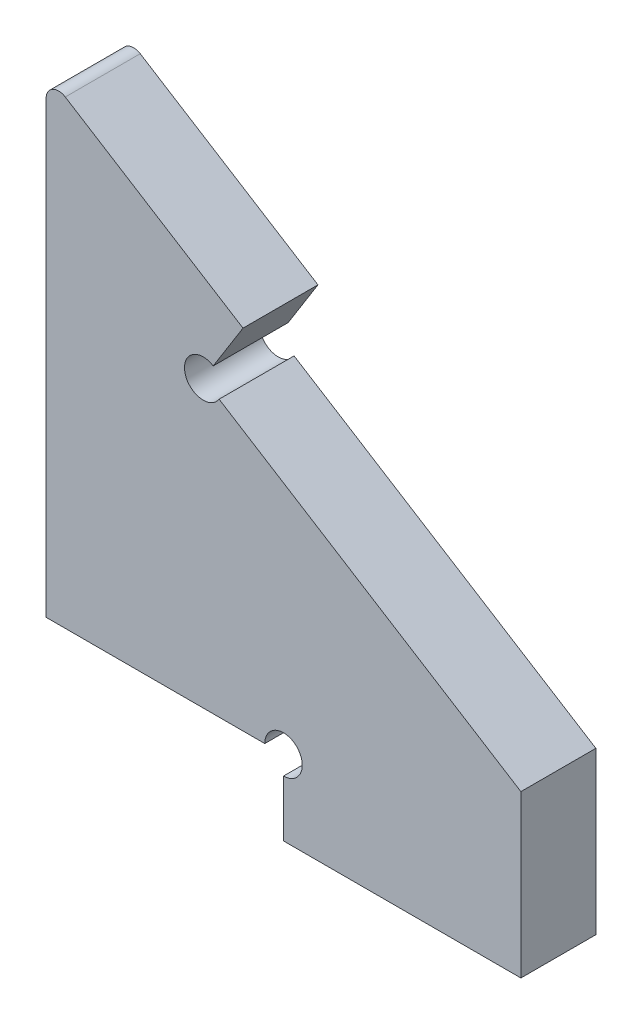
SolidWorks part; units mm, degrees
material "Plain Carbon Steel"
ref_plane "Front Plane" through (0, 0, 0) normal (0, 0, 1) x (1, 0, 0)
ref_plane "Top Plane" through (0, 0, 0) normal (0, 1, 0) x (1, 0, 0)
ref_plane "Right Plane" through (0, 0, 0) normal (1, 0, 0) x (0, 0, -1)
sketch "Sketch1" plane through (0, 0, 0) normal (0, 0, 1) x (1, 0, 0)
  line L0 (724, 125) -> (705, 125)
  line L1 (724, 120) -> (686, 120) construction
  line L2 (705, 125) -> (705, 131)
  line L3 (705, 131) -> (724, 131)
  line L4 (724, 131) -> (724, 125)
  line L5 (686, -1514) -> (686, 120) construction
  line L6 (705, 120) -> (705, 146.8902) construction
  line L7 (724, 131) -> (714, 131) construction
extrude "Boss-Extrude1" add sketch "Sketch1" along normal blind 6 from surface
sketch "Sketch2" plane through (0, 131, 0) normal (0, 1, 0) x (1, 0, 0)
  line L0 (705, 25) -> (705, 31) construction
  line L1 (686, 31) -> (724, 31)
  line L2 (686, 31) -> (686, 25)
  line L3 (686, 25) -> (724, 25)
  line L4 (724, 31) -> (724, 25)
  line L5 (686, 31) -> (724, 25) construction
  line L6 (686, 25) -> (724, 31) construction
  point P0 (705, 28)
extrude "Boss-Extrude2" add sketch "Sketch2" along normal up to surface (14 mm away)
sketch "Sketch3" plane through (0, 0, -25) normal (0, 0, 1) x (1, 0, 0)
  circle A0 centre (705, 131) radius 1.5
  dimension "D1" = 3
extrude "Cut-Extrude1" cut sketch "Sketch3" against normal through all
fillet "Fillet1" radius 1 1 edges at (686, 168.7937, -28)
sketch "Sketch4" plane through (0, 0, -25) normal (0, 0, 1) x (1, 0, 0)
  line L0 (701.7574, 158.9272) -> (698.5732, 153.8419)
  line L1 (724, 145) -> (687.5307, 167.8353) construction
  line L2 (698.5732, 153.8419) -> (724, 137.9209)
  line L3 (724, 137.9209) -> (727.1842, 143.0062)
  line L4 (701.7574, 158.9272) -> (727.1842, 143.0062)
  line L6 (724, 145) -> (724, 125) construction
  dimension "D1" = 6
  dimension "D2" = 30
extrude "Cut-Extrude3" cut sketch "Sketch4" against normal through all and the other way through all
sketch "Sketch5" plane through (0, 0, -25) normal (0, 0, 1) x (1, 0, 0)
  circle A0 centre (698.5732, 153.8419) radius 1.5
  dimension "D1" = 3
extrude "Cut-Extrude4" cut sketch "Sketch5" against normal through all
